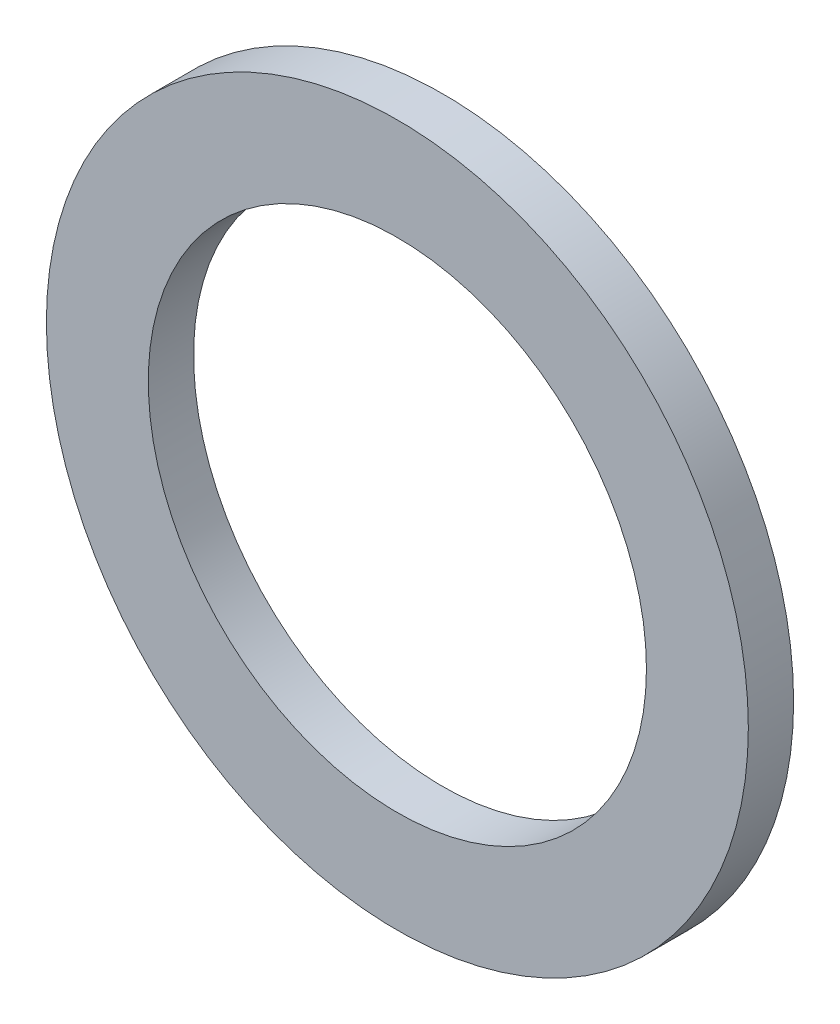
SolidWorks part; units mm, degrees
material "Plain Carbon Steel"
ref_plane "Front Plane" through (0, 0, 0) normal (0, 0, 1) x (1, 0, 0)
ref_plane "Top Plane" through (0, 0, 0) normal (0, 1, 0) x (1, 0, 0)
ref_plane "Right Plane" through (0, 0, 0) normal (1, 0, 0) x (0, 0, -1)
sketch "Sketch1" plane through (0, 0, 0) normal (0, 0, 1) x (1, 0, 0)
  circle A0 centre (0, 0) radius 24.6062
  circle A1 centre (0, 0) radius 17.4625
  dimension "D1" = 49.2125
  dimension "ID" = 34.925
extrude "Extrude1" add sketch "Sketch1" along normal mid plane 3.175
sketch "Sketch2" plane through (0, 0, 0) normal (1, 0, 0) x (0, 0, -1)
  line L0 (-1.5875, -17.4625) -> (1.5875, -17.4625) construction
  line L3 (1.5875, 17.4625) -> (-1.5875, 17.4625) construction
  line L5 (-1.5875, -17.4625) -> (1.5875, -17.4625)
  line L6 (1.5875, 17.4625) -> (-1.5875, 17.4625)
sketch "Sketch4" plane through (0, 0, 1.5875) normal (0, 0, 1) x (1, 0, 0)
  line L0 (0, 0) -> (-12.3479, 12.3479)
  line L1 (0, -1.7463) -> (0, 1.7463) construction
  circle A0 centre (0, 0) radius 17.4625 construction
  dimension "D1" = 45
